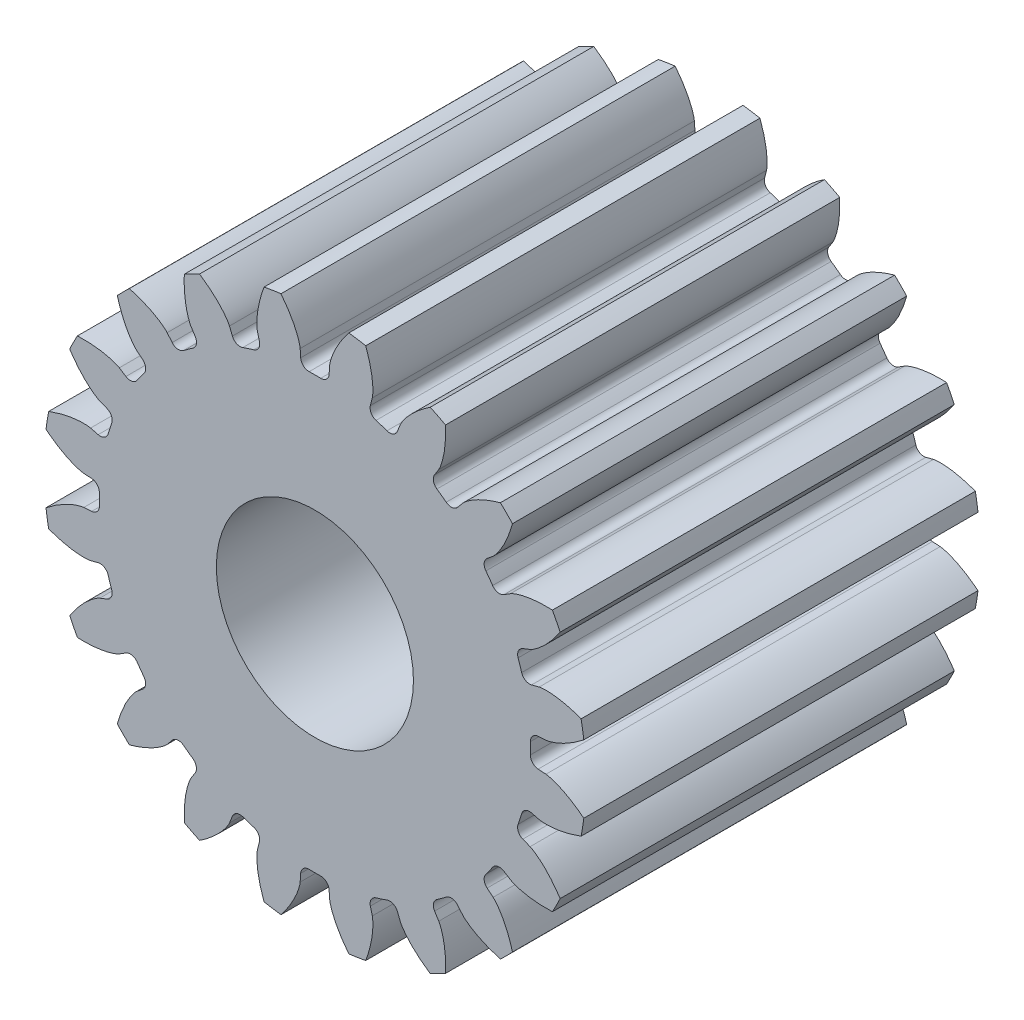
SolidWorks part; units mm, degrees
material "Plain Carbon Steel"
ref_plane "Front Plane" through (0, 0, 0) normal (0, 0, 1) x (1, 0, 0)
ref_plane "Top Plane" through (0, 0, 0) normal (0, 1, 0) x (1, 0, 0)
ref_plane "Right Plane" through (0, 0, 0) normal (1, 0, 0) x (0, 0, -1)
sketch "Sketch1" plane through (0, 0, 0) normal (0, 0, 1) x (1, 0, 0)
  line L0 (0, 0) -> (0, 7.9375) construction
  line L1 (-2.5511, 8.866) -> (2.5511, 7.009) construction
  circle A0 centre (0, 0) radius 6.9453 construction
  circle A1 centre (0, 0) radius 8.7312 construction
  circle A2 centre (0, 0) radius 7.9375 construction
  circle A3 centre (0, 0) radius 7.4588 construction
  point P8 (406.4, 0)
  point P13 (254, 0)
  dimension "OD | Outside Diameter" = 17.4625
  dimension "Root Diameter" = 13.8906
  dimension "Gear Pitch Diameter" = 15.875
  dimension "Base Diameter" = 14.9176
  dimension "Pressure Angle" = 20
  dimension "Number of Teeth" = 508
  dimension "Gear Pitch | Diametral Pitch" = 812.8
sketch "Sketch2" plane through (0, 0, 0) normal (1, 0, 0) x (0, 0, -1)
  line L0 (-6.35, 0) -> (6.35, 0) construction
  point P2 (2.3812, 0)
  point P5 (6.7469, 0)
  point P6 (-2.3812, 0)
  dimension "Length" = 12.7
  dimension "D1" = 8.7312
  dimension "D2" = 13.0969
  dimension "D3" = 8.7312
sketch "Sketch3" plane through (0, 0, 0) normal (0, 0, 1) x (1, 0, 0)
  circle A0 centre (0, 0) radius 8.7312
  circle A1 centre (0, 0) radius 8.7312 construction
extrude "Boss-Extrude1" add sketch "Sketch3" against normal up to vertex (6.35 mm away) and the other way up to vertex (6.35 mm away) up to point (0, 0, -6.35) other way up to point (0, 0, 6.35)
sketch "Sketch4" plane through (0, 0, 0) normal (0, 0, 1) x (1, 0, 0)
  line L0 (0, 0) -> (6.9313, 0.4417) construction
  line L2 (0, 0) -> (6.9313, -0.4417) construction
  line L4 (6.9313, 0.4417) -> (7.4437, 0.4743)
  line L5 (7.4437, -0.4743) -> (6.9313, -0.4417)
  arc A0 (6.9313, 0.4417) -> (6.9313, -0.4417) centre (0, 0) cw
  arc A3 (8.6626, 1.0928) -> (8.6626, -1.0928) centre (0, 0) cw
  circle A4 centre (0, 0) radius 8.7312 construction
  spline S0 degree 4 poles (7.4437, 0.4743) (7.4457, 0.4745) (7.4515, 0.475) (7.4622, 0.4763) (7.4797, 0.4789) (7.502, 0.4828) (7.5306, 0.4887) (7.5643, 0.4966) (7.6011, 0.5063) (7.6409, 0.518) (7.6805, 0.5306) (7.7199, 0.5441) (7.7589, 0.5584) (7.806, 0.5766) (7.8621, 0.5998) (7.9274, 0.6288) (8.0008, 0.664) (8.0749, 0.7023) (8.1474, 0.742) (8.22, 0.7844) (8.2897, 0.8269) (8.3615, 0.8734) (8.4273, 0.9176) (8.5003, 0.9695) (8.5589, 1.0122) (8.6353, 1.0711) (8.6802, 1.1067) (8.7324, 1.1493) (8.7553, 1.1687) (8.7695, 1.1806) knots 0 0 0 0 0 0.005377 0.015084 0.028532 0.04661 0.064855 0.092111 0.119476 0.146842 0.174209 0.201575 0.228941 0.256307 0.307035 0.361767 0.4165 0.471232 0.525964 0.580697 0.635429 0.690161 0.744894 0.799626 0.854358 0.909091 0.954545 1 1 1 1 1 construction
  spline S1 degree 4 poles (7.4437, 0.4743) (7.4457, 0.4745) (7.4515, 0.475) (7.4622, 0.4763) (7.4797, 0.4789) (7.502, 0.4828) (7.5306, 0.4887) (7.5643, 0.4966) (7.6011, 0.5063) (7.6409, 0.518) (7.6805, 0.5306) (7.7199, 0.5441) (7.7589, 0.5584) (7.806, 0.5766) (7.8621, 0.5998) (7.9274, 0.6288) (8.0008, 0.664) (8.0749, 0.7023) (8.1474, 0.742) (8.22, 0.7844) (8.2897, 0.8269) (8.3615, 0.8734) (8.4273, 0.9176) (8.5003, 0.9695) (8.5589, 1.0122) (8.6188, 1.0583) (8.6478, 1.0811) (8.6626, 1.0928) knots 0 0 0 0 0 0.005377 0.015084 0.028532 0.04661 0.064855 0.092111 0.119476 0.146842 0.174209 0.201575 0.228941 0.256307 0.307035 0.361767 0.4165 0.471232 0.525964 0.580697 0.635429 0.690161 0.744894 0.799626 0.854358 0.909091 0.909091 0.909091 0.909091 0.909091
  spline S2 degree 4 poles (7.4437, -0.4743) (7.4457, -0.4745) (7.4515, -0.475) (7.4622, -0.4763) (7.4797, -0.4789) (7.502, -0.4828) (7.5306, -0.4887) (7.5643, -0.4966) (7.6011, -0.5063) (7.6409, -0.518) (7.6805, -0.5306) (7.7199, -0.5441) (7.7589, -0.5584) (7.806, -0.5766) (7.8621, -0.5998) (7.9274, -0.6288) (8.0008, -0.664) (8.0749, -0.7023) (8.1474, -0.742) (8.22, -0.7844) (8.2897, -0.8269) (8.3615, -0.8734) (8.4273, -0.9176) (8.5003, -0.9695) (8.5589, -1.0122) (8.6353, -1.0711) (8.6802, -1.1067) (8.7324, -1.1493) (8.7553, -1.1687) (8.7695, -1.1806) knots 0 0 0 0 0 0.005377 0.015084 0.028532 0.04661 0.064855 0.092111 0.119476 0.146842 0.174209 0.201575 0.228941 0.256307 0.307035 0.361767 0.4165 0.471232 0.525964 0.580697 0.635429 0.690161 0.744894 0.799626 0.854358 0.909091 0.954545 1 1 1 1 1 construction
  spline S3 degree 4 poles (7.4437, -0.4743) (7.4457, -0.4745) (7.4515, -0.475) (7.4622, -0.4763) (7.4797, -0.4789) (7.502, -0.4828) (7.5306, -0.4887) (7.5643, -0.4966) (7.6011, -0.5063) (7.6409, -0.518) (7.6805, -0.5306) (7.7199, -0.5441) (7.7589, -0.5584) (7.806, -0.5766) (7.8621, -0.5998) (7.9274, -0.6288) (8.0008, -0.664) (8.0749, -0.7023) (8.1474, -0.742) (8.22, -0.7844) (8.2897, -0.8269) (8.3615, -0.8734) (8.4273, -0.9176) (8.5003, -0.9695) (8.5589, -1.0122) (8.6188, -1.0583) (8.6478, -1.0811) (8.6626, -1.0928) knots 0 0 0 0 0 0.005377 0.015084 0.028532 0.04661 0.064855 0.092111 0.119476 0.146842 0.174209 0.201575 0.228941 0.256307 0.307035 0.361767 0.4165 0.471232 0.525964 0.580697 0.635429 0.690161 0.744894 0.799626 0.854358 0.909091 0.909091 0.909091 0.909091 0.909091
  dimension "D1" = 13.8906
extrude "Cut-Extrude1" cut sketch "Sketch4" against normal through all both and the other way through all
fillet "Fillet1" radius 0.2663 2 edges at (6.9313, -0.4417, 0) (6.9313, 0.4417, 0)
pattern_circular "CirPattern1" count 20 over 360 about axis through (0, 0, 6.35) along (0, 0, -1) of "Cut-Extrude1", "Fillet1"
sketch "Sketch5" plane through (0, 0, 6.35) normal (0, 0, 1) x (1, 0, 0)
  point P0 (0, 0)
hole_wizard "1/4 (0.2500) Dowel Hole1" positions "Sketch5" profile "Sketch6" hole size "1/4" standard "ANSI Inch" end condition through all
sketch "Sketch6" plane through (0, 0, 6.35) normal (1, 0, 0) x (0, -1, 0)
  line L0 (0, 0) -> (0, 12.7)
  line L1 (0, 12.7) -> (3.175, 12.7)
  line L2 (3.175, 12.7) -> (3.175, 0)
  line L5 (3.175, 0) -> (0, 0)
  line L11 (0, -6.35) -> (0, 107.95) construction
  dimension "Thru Hole Dia." = 6.35
  dimension "Thru Hole Depth" = 12.7
equation "\"Root Diameter@Sketch1\"=\"Root Diameter\""
equation "\"OD | Outside Diameter@Sketch1\"=\"Outside Diameter\""
equation "\"D1@CirPattern1\"=\"Number of Teeth\""
equation "\"Diametral Pitch\"=32"
equation "\"Number of Teeth\"= 20"
equation "\"Pressure Angle\"=20"
equation "\"Pitch Diameter\"= \"Number of Teeth\" / \"Diametral Pitch\""
equation "\"Base Diameter\"= \"Pitch Diameter\" * cos ( \"Pressure Angle\" )"
equation "\"Outside Diameter\"= ( \"Number of Teeth\" + 2 ) / \"Diametral Pitch\""
equation "\"Dedendum\"= 1.25 / \"Diametral Pitch\""
equation "\"Root Diameter\"= \"Pitch Diameter\" - ( 2 * \"Dedendum\" )"
equation "\"Pitch Angle\"= 360deg / \"Number of Teeth\""
equation "\"Alpha\"= sqr ( \"Pitch Diameter\" ^ 2 - \"Base Diameter\" ^ 2 ) / \"Base Diameter\" * 180 / PI - \"Pressure Angle\""
equation "\"Beta\"= ( \"Pitch Angle\" / 4 - \"Alpha\" )"
equation "\"Phi\"= sqr ( ( \"Outside Diameter\" / 2 ) ^ 2 - ( \"Base Diameter\" / 2 ) ^ 2 ) / ( \"Base Diameter\" / 2 )"
equation "\"Addendum\"= 1 / \"Diametral Pitch\""
equation "\"WorkingDepth\"= 2 / \"Diametral Pitch\""
equation "\"WholeDepth\"= 2.25 / \"Diametral Pitch\""
equation "\"Clearance\"= 0.25 / \"Diametral Pitch\""
equation "\"ToothThickness\"= ( pi * 2 ) / \"Diametral Pitch\""
equation "\"CircularPitch\"= pi / \"Diametral Pitch\""
equation "\"Number of Teeth@Sketch1\"=\"Number of Teeth\""
equation "\"Gear Pitch | Diametral Pitch@Sketch1\"=\"Diametral Pitch\""
equation "\"Pressure Angle@Sketch1\"=\"Pressure Angle\""
equation "\"Gear Pitch Diameter@Sketch1\"=\"Pitch Diameter\""
equation "\"Base Diameter@Sketch1\"=\"Base Diameter\""
equation "\"Fillet\"= \"Clearance\" * cos ( \"Pressure Angle\" ) * tan ( ( 90 + \"Pressure Angle\" ) / 2 )"
equation "\"D1@Fillet1\"=\"Fillet\""
equation "\"D1@Sketch4\"=if( \"Base Diameter\">\"Root Diameter\",\"Root Diameter\",\"Base Diameter\"-.00001)"
equation "\"D1@Sketch2\"=\"OD | Outside Diameter@Sketch1\"*2*0.5*0.5"
equation "\"D2@Sketch2\"=\"D1@Sketch2\"*1.5"
equation "\"D3@Sketch2\"=\"D1@Sketch2\""
equation "\"Length\"= .5in"
equation "\"Length@Sketch2\"= \"Length\""
